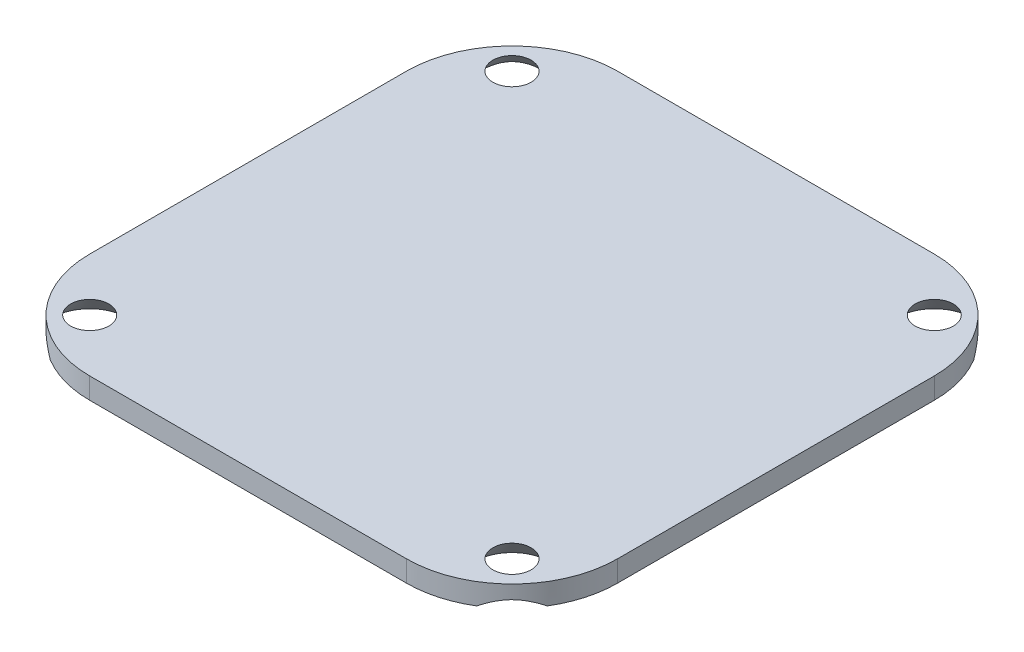
SolidWorks part; units mm, degrees
ref_plane "Front Plane" through (0, 0, 0) normal (0, 0, 1) x (1, 0, 0)
ref_plane "Top Plane" through (0, 0, 0) normal (0, 1, 0) x (1, 0, 0)
ref_plane "Right Plane" through (0, 0, 0) normal (1, 0, 0) x (0, 0, -1)
sketch "Sketch1" plane through (0, 0, 0) normal (0, 1, 0) x (1, 0, 0)
  line L1 (-25, 25) -> (25, 25)
  line L2 (-25, 25) -> (-25, -25)
  line L3 (-25, -25) -> (25, -25)
  line L4 (25, 25) -> (25, -25)
  line L5 (-25, 25) -> (25, -25) construction
  line L6 (-25, -25) -> (25, 25) construction
  point P0 (0, 0)
  dimension "D1" = 50
  dimension "D2" = 50
extrude "Boss-Extrude1" add sketch "Sketch1" along normal blind 2
sketch "Sketch2" plane through (0, 0, 0) normal (0, -1, 0) x (-1, 0, 0)
  line L0 (25, -25) -> (-25, -25) construction
  line L1 (25, 25) -> (25, -25) construction
  line L2 (-25, -25) -> (-25, 25) construction
  line L3 (-25, 25) -> (25, 25) construction
  circle A0 centre (20, -20) radius 4
  circle A1 centre (-20, -20) radius 4
  circle A2 centre (-20, 20) radius 4
  circle A3 centre (20, 20) radius 4
  point P12 (-20, 19.7906)
  point P17 (20, 20)
  point P18 (20, 20)
  dimension "D1" = 5
  dimension "D2" = 5
  dimension "D3" = 5
  dimension "D4" = 5
fillet "Fillet2" radius 10 4 edges at (25, 1, 25) (25, 1, -25) (-25, 1, -25) (-25, 1, 25)
hole_wizard "Hole1" positions "3DSketch1" profile "Sketch3" legacy
sketch3d "3DSketch1"
  point P0 (-20, 0, 20)
  point P3 (20, 0, 20)
  point P6 (20, 0, -20)
  point P9 (-20, 0, -20)
sketch "Sketch3" plane through (-20, 0, 20) normal (1, 0, 0) x (0, 0, -1)
  line L0 (0, 0) -> (0, 10)
  line L1 (0, 10) -> (1.8, 10)
  line L2 (1.8, 10) -> (1.8, 2.0131)
  line L3 (1.8, 2.0131) -> (3.55, 0)
  line L4 (3.55, 0) -> (0, 0)
  line L5 (0, -6.4453) -> (0, 115.525) construction
  line L6 (-1.8, 2.0131) -> (-3.55, 0) construction
  dimension "Diameter" = 3.6
  dimension "Depth" = 10
  dimension "C-Sink Angle" = 82
  dimension "C-Sink Diameter" = 7.1
